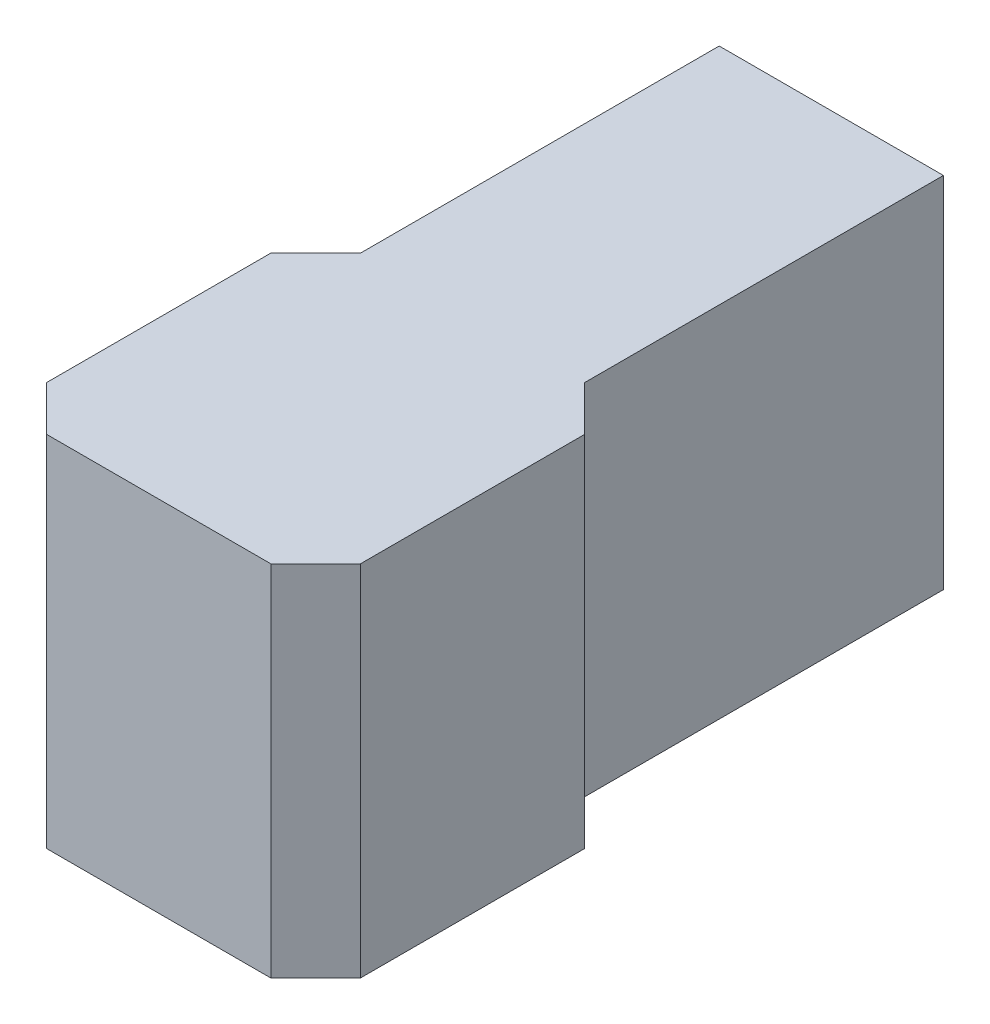
SolidWorks part; units mm, degrees
ref_plane "Front Plane" through (0, 0, 0) normal (0, 0, 1) x (1, 0, 0)
ref_plane "Top Plane" through (0, 0, 0) normal (0, 1, 0) x (1, 0, 0)
ref_plane "Right Plane" through (0, 0, 0) normal (1, 0, 0) x (0, 0, -1)
sketch "Sketch1" plane through (0, 0, 0) normal (0, 1, 0) x (1, 0, 0)
  line L1 (-35, 35) -> (35, 35)
  line L2 (-35, 35) -> (-35, -35)
  line L3 (-35, -35) -> (35, -35)
  line L4 (35, 35) -> (35, -35)
  line L5 (-35, 35) -> (35, -35) construction
  line L6 (-35, -35) -> (35, 35) construction
  point P0 (0, 0)
  dimension "D1" = 70
  dimension "D2" = 70
extrude "Boss-Extrude1" add sketch "Sketch1" along normal blind 80
chamfer "Chamfer1" distance 10 angle 45 4 edges at (-35, 40, -35) (35, 40, -35) (-35, 40, 35) (35, 40, 35)
sketch "Sketch2" plane through (0, 0, -35) normal (0, 0, -1) x (-1, 0, 0)
  line L0 (-25, 80) -> (25, 80) construction
  line L1 (-4.5, 60) -> (4.5, 60)
  line L2 (-4.5, 60) -> (-4.5, 25)
  line L3 (-4.5, 25) -> (4.5, 25)
  line L4 (4.5, 60) -> (4.5, 25)
  line L5 (-4.5, 60) -> (4.5, 25) construction
  line L6 (-4.5, 25) -> (4.5, 60) construction
  line L7 (-6, 60) -> (6, 60)
  line L8 (-6, 60) -> (-6, 70)
  line L9 (-6, 70) -> (6, 70)
  line L10 (6, 60) -> (6, 70)
  line L11 (-6, 60) -> (6, 70) construction
  line L12 (-6, 70) -> (6, 60) construction
  line L13 (-25, 0) -> (25, 0) construction
  point P0 (0, 42.5)
  point P5 (0, 65)
  point P13 (0, 25)
  dimension "D1" = 1.5
  dimension "D2" = 1.5
  dimension "D3" = 35
  dimension "D4" = 12
  dimension "D5" = 9
  dimension "D6" = 10
  dimension "D7" = 25
extrude "Cut-Extrude1" cut sketch "Sketch2" against normal blind 40 contours L7 L10 L9 L8 L1 | L4 L1 L2 L3
sketch "Sketch3" plane through (0, 0, -35) normal (0, 0, -1) x (-1, 0, 0)
  line L0 (-6, 60) -> (-6, 70) construction
  line L1 (-6, 60) -> (-6, 70)
  line L2 (6, 60) -> (6, 70) construction
  line L3 (6, 60) -> (6, 70)
  line L4 (-25, 0) -> (25, 0)
  line L5 (25, 0) -> (25, 80)
  line L6 (25, 80) -> (-25, 80)
  line L7 (-25, 80) -> (-25, 0)
  line L8 (-25, 0) -> (25, 0)
  line L9 (25, 0) -> (25, 80)
  line L10 (25, 80) -> (-25, 80)
  line L11 (-25, 80) -> (-25, 0)
  line L12 (4.5, 60) -> (6, 60) construction
  line L13 (-6, 60) -> (-4.5, 60) construction
  line L14 (-4.5, 25) -> (4.5, 25) construction
  line L15 (-4.5, 60) -> (-4.5, 25) construction
  line L16 (4.5, 60) -> (4.5, 25) construction
  line L17 (-6, 70) -> (6, 70) construction
  line L18 (4.5, 60) -> (6, 60)
  line L19 (-6, 60) -> (-4.5, 60)
  line L20 (-4.5, 25) -> (4.5, 25)
  line L21 (-4.5, 60) -> (-4.5, 25)
  line L22 (4.5, 60) -> (4.5, 25)
  line L23 (-6, 70) -> (6, 70)
  dimension "D1" = 0
extrude "Boss-Extrude2" add sketch "Sketch3" along normal blind 80
